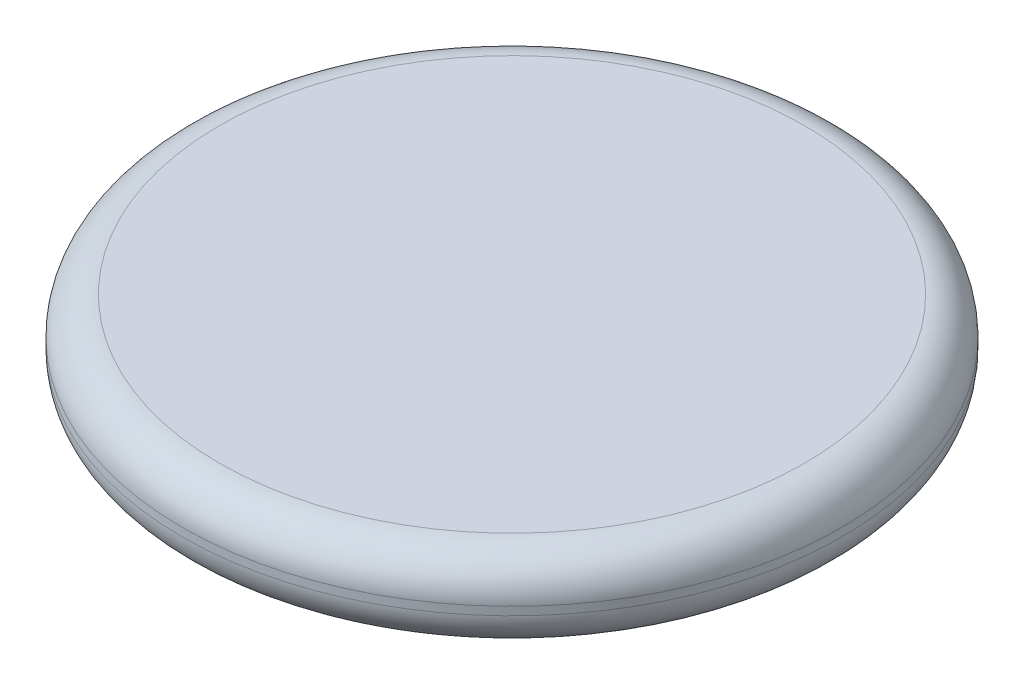
SolidWorks part; units mm, degrees
ref_plane "Front Plane" through (0, 0, 0) normal (0, 0, 1) x (1, 0, 0)
ref_plane "Top Plane" through (0, 0, 0) normal (0, 1, 0) x (1, 0, 0)
ref_plane "Right Plane" through (0, 0, 0) normal (1, 0, 0) x (0, 0, -1)
sketch "Sketch1" plane through (0, 0, 0) normal (0, 1, 0) x (1, 0, 0)
  line L1 (0, 0) -> (381, 0)
  line L2 (0, 0) -> (0, 381)
  line L3 (0, 381) -> (381, 381)
  line L4 (381, 0) -> (381, 381)
  line L5 (0, 381) -> (-203.2, 381)
  line L6 (0, 381) -> (0, 0)
  line L7 (0, 0) -> (-203.2, 0)
  line L8 (-203.2, 381) -> (-203.2, 0)
  arc A0 (381, 381) -> (0, 0) centre (0, 381) cw
  circle A1 centre (39.2386, 142.9117) radius 139.7
  circle A2 centre (0, 381) radius 101.6
  circle A3 centre (196.7476, 241.3) radius 139.7
  circle A4 centre (86.3584, 155.6826) radius 139.7
  circle A5 centre (-59.7956, 143.4044) radius 143.4044
  dimension "D1" = 381
  dimension "D2" = 381
  dimension "D3" = 203.2
extrude "Boss-Extrude2" add sketch "Sketch1" along normal blind 25.4 contours A2
fillet "Fillet1" radius 11.43 2 edges at (0, 25.4, -279.4) (0, 0, -279.4)
